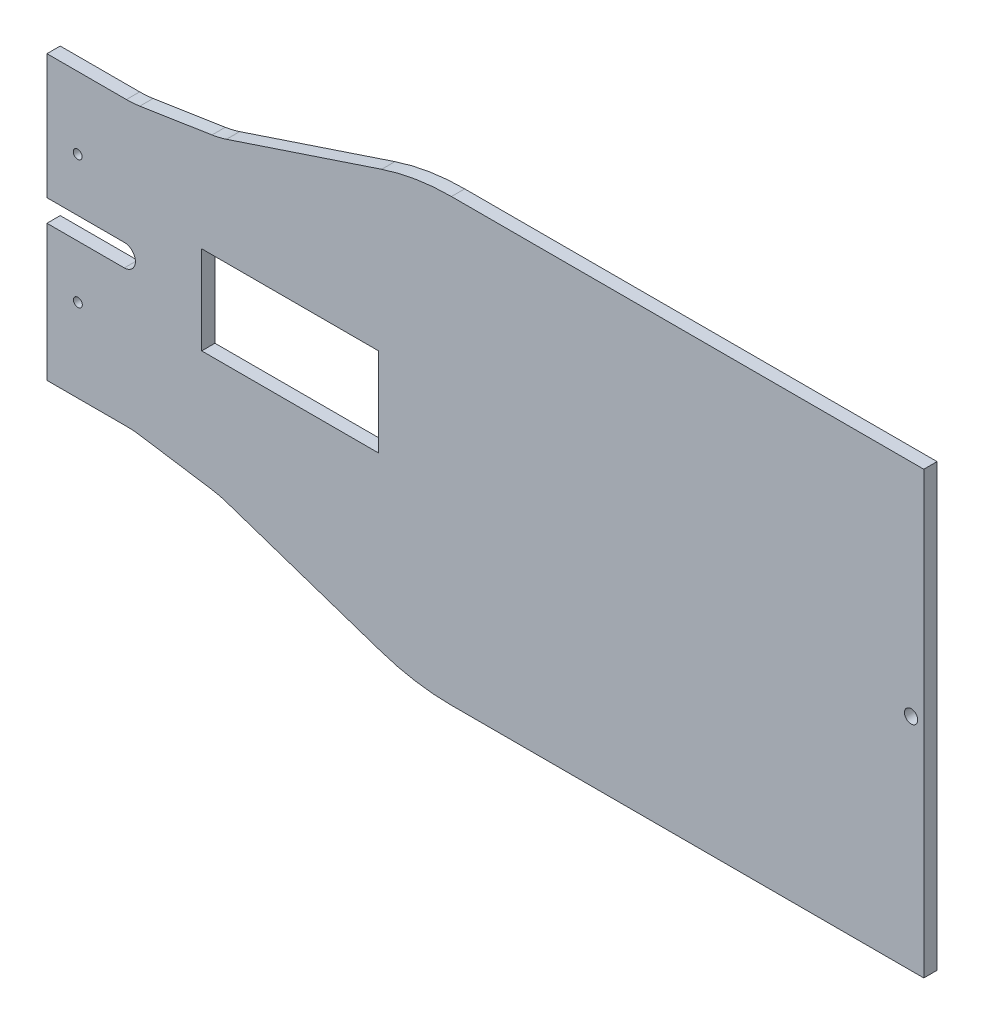
SolidWorks part; units mm, degrees
ref_plane "Plano frontal" through (0, 0, 0) normal (0, 0, 1) x (1, 0, 0)
ref_plane "Plano superior" through (0, 0, 0) normal (0, 1, 0) x (1, 0, 0)
ref_plane "Plano direito" through (0, 0, 0) normal (1, 0, 0) x (0, 0, -1)
sketch "Esboço1" plane through (0, 0, 0) normal (0, 0, 1) x (1, 0, 0)
  line L4 (130.267, 60.684) -> (130.267, -38.9721)
  line L6 (-12.6668, 60.684) -> (130.267, 60.684)
  line L13 (-12.8148, -38.9721) -> (130.267, -38.9721)
  line L21 (-96.0517, 10.9248) -> (-96.0517, 40.9248)
  line L22 (-96.0517, 10.9248) -> (-96.0517, -19.0752)
  line L23 (-96.0517, 40.9248) -> (-96.0517, 42.9248)
  line L24 (-96.0517, -19.0752) -> (-96.0517, -21.0752)
  line L31 (-96.0517, -21.0752) -> (-76.5517, -21.0752)
  line L32 (-57.0517, -24.0752) -> (-76.5517, -21.0752)
  line L33 (-57.0517, -24.0752) -> (-12.8148, -38.9721)
  line L34 (-96.0517, 42.9248) -> (-76.5517, 42.9248)
  line L35 (-76.5517, 42.9248) -> (-57.0517, 45.9248)
  line L36 (-57.0517, 45.9248) -> (-12.6668, 60.684)
  dimension "D1" = 2
  dimension "D2" = 2
extrude "Ressalto-extrusão2" add sketch "Esboço1" along normal blind 3
fillet "Filete4" radius 50 2 edges at (-12.6668, 60.684, 1.5) (-12.8148, -38.9721, 1.5)
fillet "Filete6" radius 20 4 edges at (-76.5517, -21.0752, 1.5) (-57.0517, -24.0752, 1.5) (-76.5517, 42.9248, 1.5) (-57.0517, 45.9248, 1.5)
sketch "Esboço3" plane through (0, 0, 3) normal (0, 0, 1) x (1, 0, 0)
  line L0 (130.267, 60.684) -> (130.267, -38.9721)
  line L1 (130.267, 10.856) -> (127.267, 10.856)
  circle A0 centre (127.267, 10.856) radius 1.0004
  dimension "D1" = 3
extrude "Corte-extrusão1" cut sketch "Esboço3" against normal blind 3
sketch "Esboço4" plane through (0, 0, 3) normal (0, 0, 1) x (1, 0, 0)
  line L0 (-96.0517, 42.9248) -> (-96.0517, -21.0752)
  line L1 (-96.0517, 14.7058) -> (-96.0517, 9.7058)
  line L2 (-78.5517, 9.7058) -> (-96.0517, 9.7058)
  line L3 (-78.5517, 14.7058) -> (-96.0517, 14.7058)
  line L4 (-81.0517, 12.2058) -> (-96.0517, 12.2058)
  circle A0 centre (-78.5517, 12.2058) radius 2.5
  dimension "D1" = 5
  dimension "D2" = 15
extrude "Corte-extrusão3" cut sketch "Esboço4" against normal blind 3 contours A0 L3 L0 L4 | A0 L4 L1 L2 | A0
sketch "Esboço5" plane through (0, 0, 3) normal (0, 0, 1) x (1, 0, 0)
  line L0 (-96.0517, -5.6847) -> (-89.0517, -5.6847)
  line L1 (-96.0517, 9.7058) -> (-96.0517, -21.0752) construction
  line L2 (-96.0517, 28.8153) -> (-89.0517, 28.8153)
  line L3 (-96.0517, 42.9248) -> (-96.0517, 14.7058) construction
  line L4 (-89.0517, 14.7058) -> (-89.0517, 25.7058)
  line L5 (-78.5517, 14.7058) -> (-96.0517, 14.7058) construction
  line L6 (-89.0517, 9.7058) -> (-89.0517, -1.2942)
  line L7 (-78.5517, 9.7058) -> (-96.0517, 9.7058) construction
  line L8 (-89.0517, -1.2942) -> (-85.1918, -1.2942)
  line L9 (-89.0517, 25.7058) -> (-85.7848, 25.7058)
  circle A0 centre (-89.1021, 26.7045) radius 1
  circle A1 centre (-89.0594, -2.2942) radius 1
  dimension "D4" = 2
  dimension "D5" = 2
  dimension "D1" = 7
  dimension "D2" = 11
  dimension "D3" = 11
extrude "Corte-extrusão4" cut sketch "Esboço5" against normal blind 3 contours A1 | A0
sketch "Esboço6" plane through (0, 0, 3) normal (0, 0, 1) x (1, 0, 0)
  line L0 (-4.622, -38.9721) -> (130.267, -38.9721) construction
  line L1 (130.267, 60.684) -> (102.267, 60.684)
  line L2 (130.267, 60.684) -> (130.267, -38.9721)
  line L3 (130.267, -38.9721) -> (102.267, -38.9721)
  line L4 (102.267, 60.684) -> (102.267, -38.9721)
  dimension "D1" = 28
extrude "Corte-extrusão5" cut sketch "Esboço6" against normal blind 10
sketch "Esboço7" plane through (0, 0, 3) normal (0, 0, 1) x (1, 0, 0)
  line L0 (102.267, 10.856) -> (99.4007, 10.856)
  line L3 (102.267, 60.684) -> (102.267, -38.9721) construction
  circle A0 centre (99.4007, 10.856) radius 1.5
  dimension "D1" = 3
extrude "Corte-extrusão6" cut sketch "Esboço7" against normal blind 10
sketch "Esboço8" plane through (0, 0, 3) normal (0, 0, 1) x (1, 0, 0)
  line L4 (-61.0517, 22.2058) -> (-21.0517, 22.2058)
  line L5 (-61.0517, 22.2058) -> (-61.0517, 2.2058)
  line L6 (-61.0517, 2.2058) -> (-21.0517, 2.2058)
  line L7 (-21.0517, 22.2058) -> (-21.0517, 2.2058)
  dimension "D4" = 40
extrude "Corte-extrusão7" cut sketch "Esboço8" against normal blind 10
